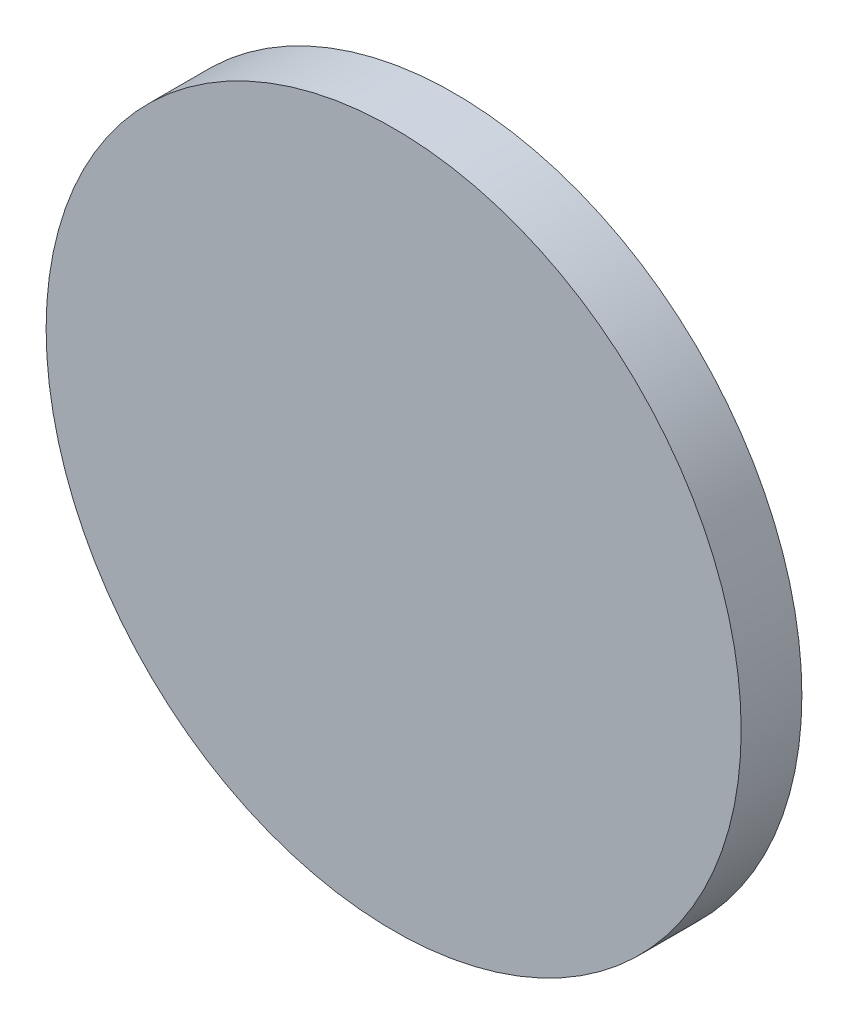
SolidWorks part; units mm, degrees
ref_plane "Front Plane" through (0, 0, 0) normal (0, 0, 1) x (1, 0, 0)
ref_plane "Top Plane" through (0, 0, 0) normal (0, 1, 0) x (1, 0, 0)
ref_plane "Right Plane" through (0, 0, 0) normal (1, 0, 0) x (0, 0, -1)
sketch "Sketch2" plane through (0, 0, 0) normal (0, 0, 1) x (1, 0, 0)
  circle A0 centre (0, 0) radius 11.45
  dimension "D1" = 22.9
extrude "Boss-Extrude1" add sketch "Sketch2" along normal blind 2
